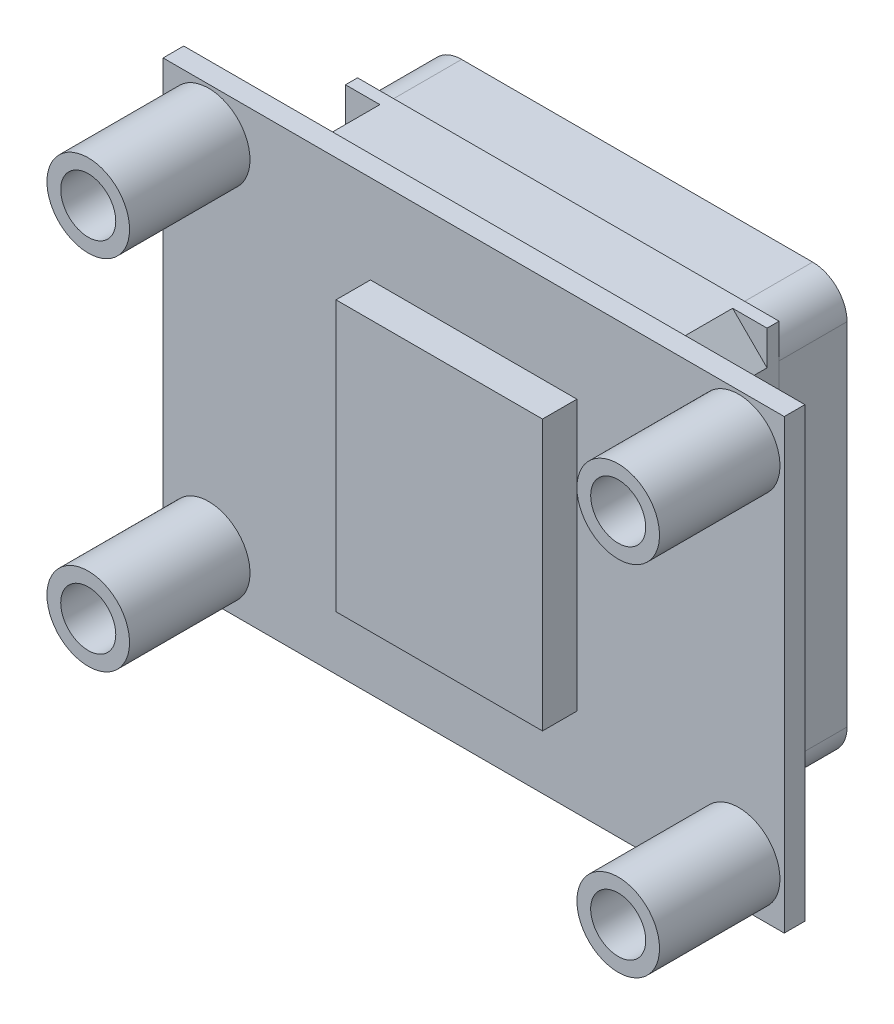
SolidWorks part; units mm, degrees
ref_plane "Front Plane" through (0, 0, 0) normal (0, 0, 1) x (1, 0, 0)
ref_plane "Top Plane" through (0, 0, 0) normal (0, 1, 0) x (1, 0, 0)
ref_plane "Right Plane" through (0, 0, 0) normal (1, 0, 0) x (0, 0, -1)
sketch "Sketch1" plane through (0, 0, 0) normal (0, 0, 1) x (1, 0, 0)
  line L0 (0, 0) -> (0, 10.4) construction
  line L1 (18.05, -13) -> (-18.05, -13)
  line L2 (18.05, -13) -> (18.05, 13)
  line L3 (18.05, 13) -> (-18.05, 13)
  line L4 (-18.05, -13) -> (-18.05, 13)
  line L5 (18.05, -13) -> (-18.05, 13) construction
  line L6 (18.05, 13) -> (-18.05, -13) construction
  line L7 (0, 10.4) -> (-15.4, 10.4) construction
  line L8 (0, 0) -> (-8.8627, 0) construction
  circle A0 centre (-15.4, 10.4) radius 1.6
  circle A1 centre (15.4, 10.4) radius 1.6
  circle A2 centre (15.4, -10.4) radius 1.6
  circle A3 centre (-15.4, -10.4) radius 1.6
  point P0 (0, 0)
  dimension "D5" = 3.2
  dimension "D1" = 36.1
  dimension "D2" = 26
  dimension "D3" = 10.4
  dimension "D4" = 15.4
extrude "Boss-Extrude1" add sketch "Sketch1" along normal blind 1.2
ref_plane "Plane1" through (0, 0, 0) normal (0, 0, -1) x (-1, 0, 0)
sketch "Sketch2" plane through (0, 0, 0) normal (0, 0, -1) x (-1, 0, 0)
  line L0 (-18.05, 0) -> (-12.85, 0) construction
  line L1 (-18.05, -13) -> (-18.05, 13) construction
  line L2 (18.05, 0) -> (12.65, 0) construction
  line L3 (18.05, 13) -> (18.05, -13) construction
  line L4 (-12.85, 0) -> (12.65, 0) construction
  line L5 (-10.35, 12.25) -> (-12.35, 10.25)
  line L6 (10.15, -12.25) -> (-10.35, -12.25)
  line L7 (12.15, -10.25) -> (12.15, 10.25)
  line L8 (10.15, 12.25) -> (-10.35, 12.25)
  line L9 (-12.35, -10.25) -> (-12.35, 10.25)
  line L10 (12.15, -12.25) -> (-12.35, 12.25) construction
  line L11 (12.15, 12.25) -> (-12.35, -12.25) construction
  line L12 (12.15, 10.25) -> (10.15, 12.25)
  line L13 (10.15, -12.25) -> (12.15, -10.25)
  line L14 (-10.35, -12.25) -> (-12.35, -10.25)
  point P9 (-0.1, 0)
  dimension "D1" = 5.2
  dimension "D2" = 5.4
  dimension "D3" = 24.5
  dimension "D4" = 24.5
extrude "Boss-Extrude2" add sketch "Sketch2" along normal blind 3.5
ref_plane "Plane2" through (0, 0, -3.5) normal (0, 0, -1) x (-1, 0, 0)
sketch "Sketch3" plane through (0, 0, -3.5) normal (0, 0, -1) x (-1, 0, 0)
  line L0 (-12.35, 0) -> (12.15, 0) construction
  line L1 (-12.35, 10.25) -> (-12.35, -10.25) construction
  line L2 (12.15, -10.25) -> (12.15, 10.25) construction
  line L4 (12.15, -12.25) -> (-12.35, -12.25)
  line L5 (12.15, -12.25) -> (12.15, 12.25)
  line L6 (12.15, 12.25) -> (-12.35, 12.25)
  line L7 (-12.35, -12.25) -> (-12.35, 12.25)
  line L8 (12.15, -12.25) -> (-12.35, 12.25) construction
  line L9 (12.15, 12.25) -> (-12.35, -12.25) construction
  point P6 (-0.1, 0)
  dimension "D1" = 24.5
extrude "Boss-Extrude3" add sketch "Sketch3" along normal blind 0.7
ref_plane "Plane3" through (0, 0, -4.2) normal (0, 0, -1) x (-1, 0, 0)
sketch "Sketch4" plane through (0, 0, -4.2) normal (0, 0, -1) x (-1, 0, 0)
  line L0 (-12.35, 0) -> (12.15, 0) construction
  line L1 (-12.35, 10.25) -> (-12.35, -10.25) construction
  line L2 (12.15, -10.25) -> (12.15, 10.25) construction
  line L4 (10.1, -12.2) -> (-10.3, -12.2)
  line L5 (12.1, -10.2) -> (12.1, 10.2)
  line L6 (10.1, 12.2) -> (-10.3, 12.2)
  line L7 (-12.3, -10.2) -> (-12.3, 10.2)
  line L8 (12.1, -12.2) -> (-12.3, 12.2) construction
  line L9 (12.1, 12.2) -> (-12.3, -12.2) construction
  arc A0 (12.1, 10.2) -> (10.1, 12.2) centre (10.1, 10.2) ccw
  arc A1 (12.1, -10.2) -> (10.1, -12.2) centre (10.1, -10.2) cw
  arc A2 (-10.3, -12.2) -> (-12.3, -10.2) centre (-10.3, -10.2) cw
  arc A3 (-12.3, 10.2) -> (-10.3, 12.2) centre (-10.3, 10.2) cw
  point P6 (-0.1, 0)
  dimension "D3" = 2
  dimension "D1" = 24.4
  dimension "D2" = 24.4
extrude "Boss-Extrude5" add sketch "Sketch4" along normal blind 4
ref_plane "Plane4" through (0, 0, -8.2) normal (0, 0, -1) x (-1, 0, 0)
sketch "Sketch5" plane through (0, 0, -8.2) normal (0, 0, -1) x (-1, 0, 0)
  line L0 (-12.3, 0) -> (12.15, 0) construction
  line L1 (-12.3, 10.2) -> (-12.3, -10.2) construction
  line L2 (12.15, -10.25) -> (12.15, 10.25) construction
  line L4 (9.5, -11.5) -> (-9.5, -11.5)
  line L5 (11.5, -9.5) -> (11.5, 9.5)
  line L6 (9.5, 11.5) -> (-9.5, 11.5)
  line L7 (-11.5, -9.5) -> (-11.5, 9.5)
  line L8 (11.5, -11.5) -> (-11.5, 11.5) construction
  line L9 (11.5, 11.5) -> (-11.5, -11.5) construction
  arc A0 (11.5, 9.5) -> (9.5, 11.5) centre (9.5, 9.5) ccw
  arc A1 (11.5, -9.5) -> (9.5, -11.5) centre (9.5, -9.5) cw
  arc A2 (-9.5, -11.5) -> (-11.5, -9.5) centre (-9.5, -9.5) cw
  arc A3 (-11.5, 9.5) -> (-9.5, 11.5) centre (-9.5, 9.5) cw
  point P6 (0, 0)
  dimension "D3" = 2
  dimension "D1" = 23
  dimension "D2" = 23
extrude "Boss-Extrude6" add sketch "Sketch5" along normal blind 0.1
ref_plane "Plane5" through (0, 0, -8.3) normal (0, 0, -1) x (-1, 0, 0)
sketch "Sketch6" plane through (0, 0, -8.3) normal (0, 0, -1) x (-1, 0, 0)
  line L0 (0, 11.5) -> (0, -11.5) construction
  line L1 (9.5, 11.5) -> (-9.5, 11.5) construction
  line L2 (-9.5, -11.5) -> (9.5, -11.5) construction
  line L3 (0, 0) -> (1, 0) construction
  circle A0 centre (1, 0) radius 0.9074
  dimension "D1" = 1
extrude "Boss-Extrude7" add sketch "Sketch6" along normal blind 0.5
ref_plane "Plane6" through (0, 0, 1.2) normal (0, 0, 1) x (1, 0, 0)
sketch "Sketch7" plane through (0, 0, 1.2) normal (0, 0, 1) x (1, 0, 0)
  line L0 (0, 13) -> (0, -13) construction
  line L1 (18.05, 13) -> (-18.05, 13) construction
  line L2 (-18.05, -13) -> (18.05, -13) construction
  line L4 (6, -7.85) -> (-6, -7.85)
  line L5 (6, -7.85) -> (6, 7.85)
  line L6 (6, 7.85) -> (-6, 7.85)
  line L7 (-6, -7.85) -> (-6, 7.85)
  line L8 (6, -7.85) -> (-6, 7.85) construction
  line L9 (6, 7.85) -> (-6, -7.85) construction
  point P6 (0, 0)
  dimension "D1" = 12
  dimension "D2" = 15.7
extrude "Boss-Extrude8" add sketch "Sketch7" along normal blind 2
ref_plane "Plane7" through (0, 0, 1.2) normal (0, 0, 1) x (1, 0, 0)
sketch "Sketch8" plane through (0, 0, 1.2) normal (0, 0, 1) x (1, 0, 0)
  line L0 (0, 0) -> (0, 10.4) construction
  line L1 (0, 0) -> (-10.0873, 0) construction
  circle A0 centre (-15.4, 10.4) radius 2.4
  circle A1 centre (15.4, 10.4) radius 2.4
  circle A2 centre (15.4, -10.4) radius 2.4
  circle A3 centre (-15.4, -10.4) radius 2.4
  dimension "D1" = 4.8
extrude "Boss-Extrude9" add sketch "Sketch8" along normal blind 7
ref_plane "Plane8" through (0, 0, 8.2) normal (0, 0, 1) x (1, 0, 0)
sketch "Sketch9" plane through (0, 0, 8.2) normal (0, 0, 1) x (1, 0, 0)
  circle A0 centre (-15.4, 10.4) radius 1.6
  circle A1 centre (-15.4, -10.4) radius 1.6
  circle A2 centre (15.4, -10.4) radius 1.6
  circle A3 centre (15.4, 10.4) radius 1.6
  dimension "D1" = 3.2
  dimension "D2" = 3.2
  dimension "D3" = 3.2
  dimension "D4" = 3.2
extrude "Cut-Extrude3" cut sketch "Sketch9" against normal through all
